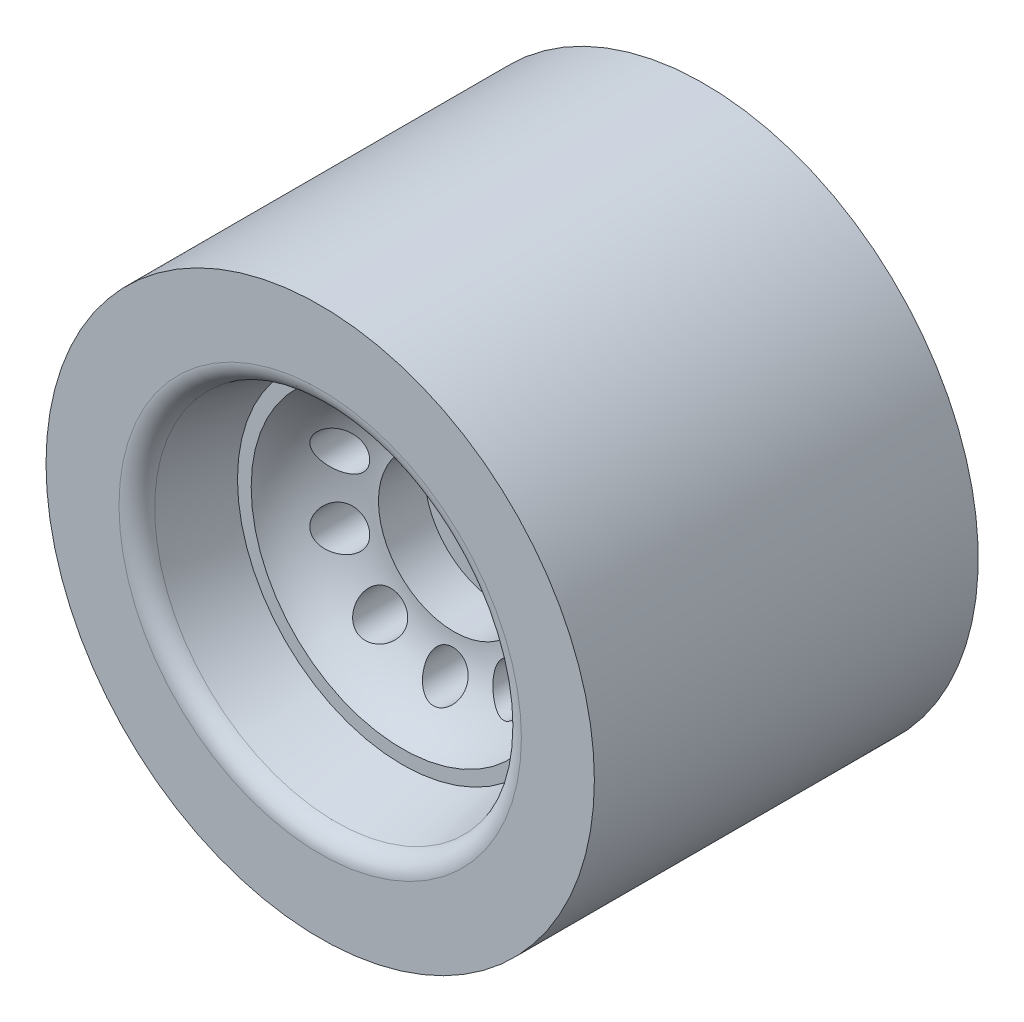
SolidWorks part; units mm, degrees
material "폴리우레탄(11671)"
ref_plane "정면" through (0, 0, 0) normal (0, 0, 1) x (1, 0, 0)
ref_plane "윗면" through (0, 0, 0) normal (0, 1, 0) x (1, 0, 0)
ref_plane "우측면" through (0, 0, 0) normal (1, 0, 0) x (0, 0, -1)
sketch "스케치1" plane through (0, 0, 0) normal (0, 0, 1) x (1, 0, 0)
  circle A0 centre (0, 0) radius 40
  dimension "D1" = 80
extrude "보스-돌출1" add sketch "스케치1" along normal mid plane 56
sketch "스케치2" plane through (0, 0, 28) normal (0, 0, 1) x (1, 0, 0)
  circle A0 centre (0, 0) radius 8.5
  dimension "D1" = 17
extrude "컷-돌출1" cut sketch "스케치2" against normal through all
sketch "스케치4" plane through (0, 0, 0) normal (1, 0, 0) x (0, 0, -1)
  line L0 (28, 0) -> (-28, 0) construction
  line L1 (28, -40) -> (28, 40) construction
  line L2 (-28, 40) -> (-28, -40) construction
  line L3 (0, 0) -> (0, -40) construction
  line L4 (-28, -40) -> (28, -40) construction
  line L5 (28, 40) -> (26.6, 33.9)
  line L7 (15.1, 0) -> (28, 0)
  line L8 (15.1, 0) -> (15.1, 11)
  line L9 (26.6, 33.9) -> (25.6, 33.4)
  line L10 (28, 0) -> (28, 40)
  line L11 (-28, 0) -> (-28, 27)
  line L12 (-28, 27) -> (-16.0084, 24.06)
  line L13 (-8.5, 11) -> (-8.5, 0)
  line L14 (-8.5, 0) -> (-28, 0)
  line L15 (-16.0084, 24.06) -> (-16.0084, 22.06)
  arc A0 (22.6084, 22.06) -> (24.2058, 28.6555) centre (43.7359, 20.4341) cw
  arc A1 (15.1, 11) -> (22.6084, 22.06) centre (27, 11) cw
  arc A2 (24.2058, 28.6555) -> (25.6, 33.4) centre (3.9291, 37.191) ccw
  arc A3 (-16.0084, 22.06) -> (-8.5, 11) centre (-20.4, 11) cw
  dimension "D5" = 11.9
  dimension "D4" = 0.5
  dimension "D9" = 21.19
  dimension "D12" = 22
  dimension "D14" = 13
  dimension "D13" = 11.9
  dimension "D2" = 22.06
  dimension "D3" = 6.1
  dimension "D6" = 11
  dimension "D7" = 11.5
  dimension "D8" = 1
  dimension "D15" = 19.5
  dimension "D16" = 2
  dimension "D17" = 1.4
  dimension "D18" = 11.3445
revolve "컷-회전1" cut sketch "스케치4" angle 360 about L0
sketch "스케치5" plane through (0, 0, 0) normal (0, 0, 1) x (1, 0, 0)
  line L0 (0, 0) -> (0, 40) construction
  circle A0 centre (0, 0) radius 40 construction
  circle A1 centre (0, 15.875) radius 3
  dimension "D1" = 6
  dimension "D2" = 15.875
extrude "컷-돌출2" cut sketch "스케치5" against normal through all both and the other way through all
pattern_circular "원형 패턴1" count 10 over 360 about axis through (0, 0, 0) along (0, 0, 1) of "컷-돌출2"
fillet "필렛1" radius 3 1 edges at (-27, 0, 28)
sketch "스케치6" plane through (0, 0, 8.5) normal (0, 0, 1) x (1, 0, 0)
  circle A0 centre (0, 0) radius 11
  dimension "D1" = 22
extrude "컷-돌출3" cut sketch "스케치6" against normal blind 6.75
sketch "스케치7" plane through (0, 0, -15.1) normal (0, 0, -1) x (-1, 0, 0)
  circle A0 centre (0, 0) radius 11
  dimension "D1" = 22
extrude "컷-돌출4" cut sketch "스케치7" against normal blind 6.75
